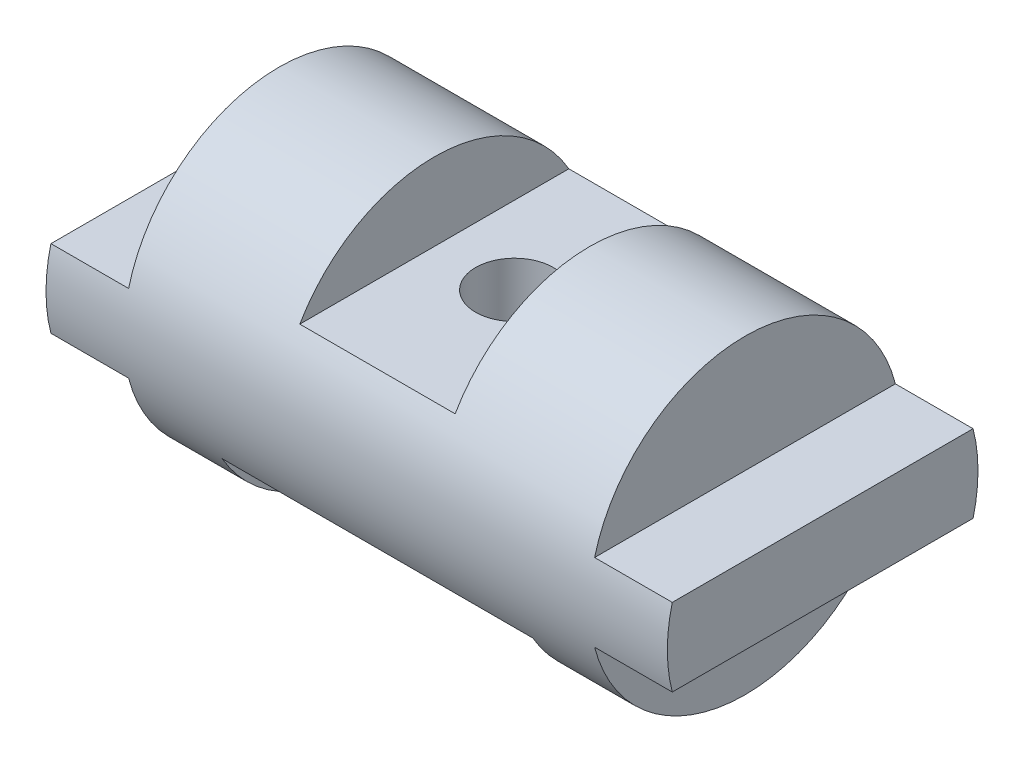
SolidWorks part; units mm, degrees
ref_plane "Front Plane" through (0, 0, 0) normal (0, 0, 1) x (1, 0, 0)
ref_plane "Top Plane" through (0, 0, 0) normal (0, 1, 0) x (1, 0, 0)
ref_plane "Right Plane" through (0, 0, 0) normal (1, 0, 0) x (0, 0, -1)
sketch "Sketch1" plane through (0, 0, 0) normal (1, 0, 0) x (0, 0, -1)
  circle A0 centre (0, 0) radius 20
  point P2 (0, 0)
  dimension "D1" = 40
extrude "Boss-Extrude1" add sketch "Sketch1" along normal blind 80
sketch "Sketch2" plane through (0, 0, 0) normal (0, 0, 1) x (1, 0, 0)
  line L0 (30, 20) -> (30, 10)
  line L1 (80, 20) -> (0, 20) construction
  line L2 (30, 10) -> (50, 10)
  line L3 (50, 10) -> (50, 20)
  line L4 (50, 20) -> (30, 20)
  line L5 (0, 5) -> (10, 5)
  line L6 (0, 20) -> (0, -20) construction
  line L7 (10, 5) -> (10, 20)
  line L8 (10, 20) -> (0, 20)
  line L9 (0, 20) -> (0, 5)
  line L10 (0, -5) -> (10, -5)
  line L11 (10, -5) -> (10, -20)
  line L12 (0, -20) -> (80, -20) construction
  line L13 (10, -20) -> (0, -20)
  line L14 (0, -20) -> (0, -5)
  line L15 (70, 20) -> (70, 5)
  line L16 (70, 5) -> (80, 5)
  line L17 (80, -20) -> (80, 20) construction
  line L18 (70, 20) -> (80, 20)
  line L19 (80, 20) -> (80, 5)
  line L20 (70, -5) -> (80, -5)
  line L21 (80, -5) -> (80, -20)
  line L22 (80, -20) -> (70, -20)
  line L23 (70, -20) -> (70, -5)
  line L24 (20, -20) -> (20, -10)
  line L25 (20, -10) -> (60, -10)
  line L26 (60, -10) -> (60, -20)
  line L27 (60, -20) -> (20, -20)
  point P36 (40, 20)
  point P37 (40, -20)
  dimension "D1" = 10
  dimension "D2" = 15
  dimension "D3" = 20
  dimension "D4" = 10
  dimension "D5" = 40
  dimension "D6" = 10
extrude "Cut-Extrude1" cut sketch "Sketch2" against normal up to next and the other way up to next
sketch "Sketch3" plane through (0, 10, 0) normal (0, 1, 0) x (1, 0, 0)
  line L0 (30, -17.3205) -> (30, 17.3205) construction
  line L1 (50, 17.3205) -> (30, 17.3205) construction
  circle A0 centre (40, 0.3205) radius 5
  dimension "D1" = 10
  dimension "D2" = 10
  dimension "D3" = 17
extrude "Cut-Extrude2" cut sketch "Sketch3" against normal up to next
